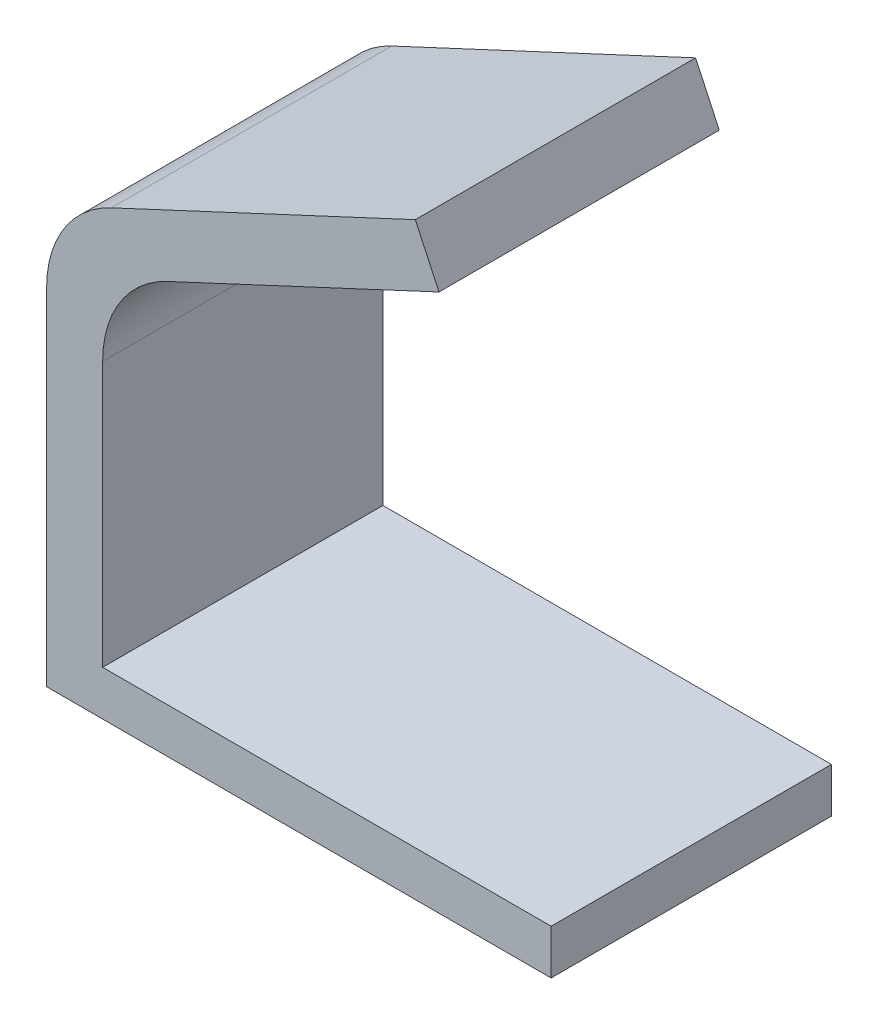
SolidWorks part; units mm, degrees
ref_plane "Alzado" through (0, 0, 0) normal (0, 0, 1) x (1, 0, 0)
ref_plane "Planta" through (0, 0, 0) normal (0, 1, 0) x (1, 0, 0)
ref_plane "Vista lateral" through (0, 0, 0) normal (1, 0, 0) x (0, 0, -1)
sketch "Croquis1" plane through (0, 0, 0) normal (0, 0, 1) x (1, 0, 0)
  line L0 (0, 8) -> (0, 0)
  line L1 (0, 0) -> (-90, 0)
  line L2 (-90, 0) -> (-90, 74.3707)
  line L3 (-80, 8) -> (-20, 8) construction
  line L4 (-80, 68) -> (-80, 8)
  line L5 (-80, 8) -> (0, 8)
  line L6 (-80, 68) -> (-20, 95.9785)
  line L7 (-20, 95.9785) -> (-24.2262, 105.0415)
  line L8 (-24.2262, 105.0415) -> (-90, 74.3707)
  line L9 (-20, 8) -> (-20, 120.6805) construction
  dimension "D1" = 8
  dimension "D2" = 80
  dimension "D3" = 10
  dimension "D4" = 10
  dimension "D5" = 60
  dimension "D6" = 20
  dimension "D7" = 25
extrude "Saliente-Extruir1" add sketch "Croquis1" along normal mid plane 50
fillet "Redondeo1" radius 20 2 edges at (-80, 68, 0) (-90, 74.3707, 0)
